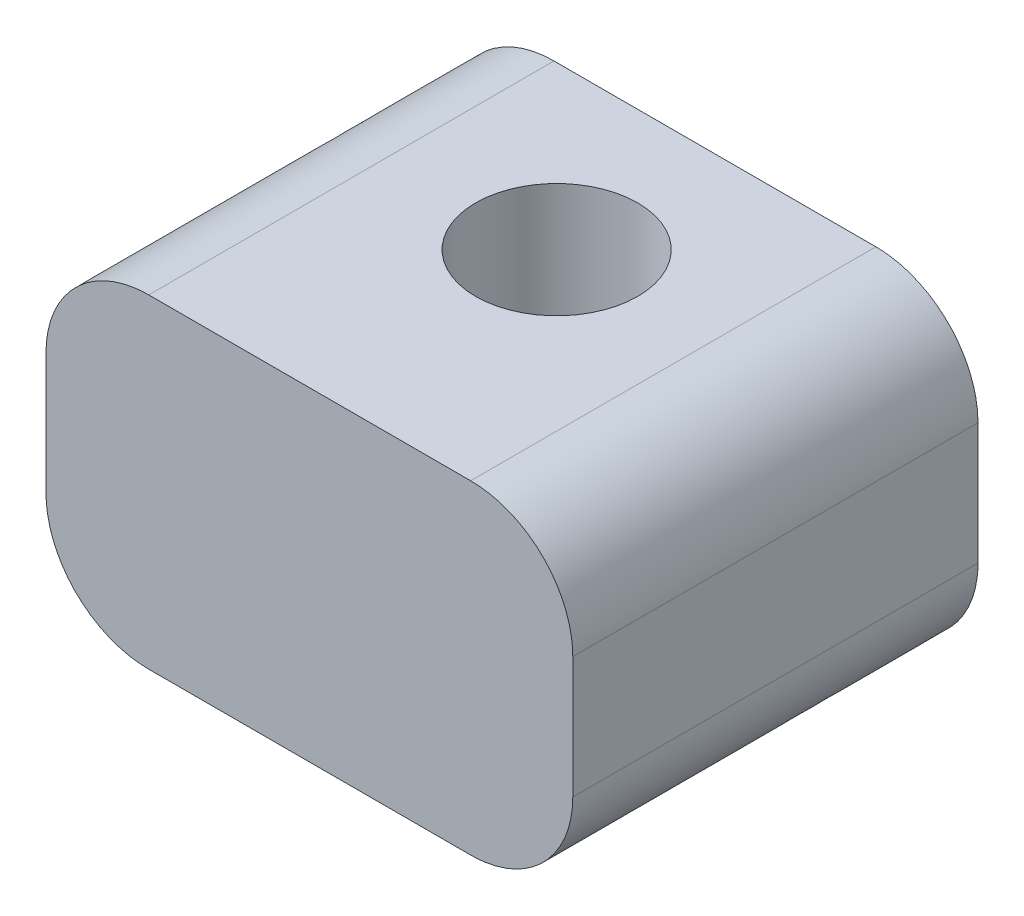
SolidWorks part; units mm, degrees
ref_plane "Plan de face" through (0, 0, 0) normal (0, 0, 1) x (1, 0, 0)
ref_plane "Plan de dessus" through (0, 0, 0) normal (0, 1, 0) x (1, 0, 0)
ref_plane "Plan de droite" through (0, 0, 0) normal (1, 0, 0) x (0, 0, -1)
sketch "Esquisse1" plane through (0, 0, 0) normal (0, 0, 1) x (1, 0, 0)
  line L0 (38.7855, 40.6141) -> (-40.6517, 40.6141)
  line L1 (-40.6517, -39.3859) -> (38.7855, -39.3859)
  line L2 (-66.0178, 15.6141) -> (-66.0178, -14.3859)
  line L3 (63.9822, -14.3859) -> (63.9822, 15.6141)
  spline S0 degree 3 poles (-40.6517, 40.6141) (-42.3144, 40.6141) (-43.95, 40.4545) (-46.3643, 39.9852) (-47.1625, 39.7902) (-48.7455, 39.3212) (-49.5335, 39.0456) (-51.8287, 38.1155) (-53.2814, 37.3559) (-55.3454, 36.0087) (-56.0141, 35.5248) (-57.3112, 34.4845) (-57.9289, 33.9366) (-59.6913, 32.2135) (-60.7465, 30.9591) (-62.1457, 28.9152) (-62.5826, 28.2035) (-63.3749, 26.7553) (-63.7328, 26.0159) (-64.3733, 24.5068) (-64.6559, 23.7372) (-65.1449, 22.1674) (-65.3517, 21.3656) (-65.851, 18.9232) (-66.0178, 17.2774) (-66.0178, 15.6141) knots 0 0 0 0 0.125 0.125 0.1875 0.1875 0.25 0.25 0.375 0.375 0.4375 0.4375 0.5 0.5 0.625 0.625 0.6875 0.6875 0.75 0.75 0.8125 0.8125 0.875 0.875 1 1 1 1
  spline S1 degree 3 poles (-66.0178, -14.3859) (-66.0178, -16.0489) (-65.8511, -17.6833) (-65.3617, -20.0941) (-65.1584, -20.8909) (-64.6695, -22.4703) (-64.383, -23.2539) (-63.4189, -25.5311) (-62.6329, -26.97) (-61.4734, -28.6704) (-61.2326, -29.0056) (-60.7328, -29.6658) (-60.4732, -29.9916) (-59.6752, -30.9436) (-59.1156, -31.5475) (-57.3566, -33.2698) (-56.0777, -34.2996) (-54.3434, -35.4353) (-53.9899, -35.6547) (-53.2767, -36.0734) (-52.9162, -36.2733) (-51.8231, -36.8456) (-50.3347, -37.5353) (-48.7852, -38.0799) (-47.2049, -38.551) (-46.3956, -38.7503) (-43.9577, -39.2265) (-42.314, -39.3859) (-40.6517, -39.3859) knots 0 0 0 0 0.125 0.125 0.1875 0.1875 0.25 0.25 0.375 0.375 0.40625 0.40625 0.4375 0.4375 0.5 0.5 0.625 0.625 0.65625 0.65625 0.6875 0.6875 0.75 0.8125 0.8125 0.875 0.875 1 1 1 1
  spline S2 degree 3 poles (38.7855, -39.3859) (40.4427, -39.3859) (42.0725, -39.2254) (44.4779, -38.7532) (45.2731, -38.557) (46.85, -38.0851) (47.6344, -37.808) (49.9178, -36.8733) (51.3625, -36.1103) (53.4143, -34.7577) (54.0799, -34.271) (55.3664, -33.2286) (55.9787, -32.68) (57.7259, -30.9545) (58.7717, -29.6987) (60.1578, -27.6532) (60.5896, -26.9422) (61.3723, -25.4968) (62.0795, -24.0208) (62.638, -22.4845) (63.1211, -20.9176) (63.3256, -20.1162) (63.8177, -17.6832) (63.9822, -16.0434) (63.9822, -14.3859) knots 0 0 0 0 0.125 0.125 0.1875 0.1875 0.25 0.25 0.375 0.375 0.4375 0.4375 0.5 0.5 0.625 0.625 0.6875 0.6875 0.75 0.8125 0.8125 0.875 0.875 1 1 1 1
  spline S3 degree 3 poles (63.9822, 15.6141) (63.9822, 17.2713) (63.8178, 18.9005) (63.3348, 21.304) (63.1341, 22.0984) (62.6516, 23.6734) (62.3685, 24.4555) (61.4156, 26.7293) (60.6385, 28.1665) (59.4915, 29.8658) (59.2532, 30.2007) (58.7587, 30.8607) (58.5017, 31.1865) (57.7105, 32.1401) (57.1555, 32.7451) (55.4107, 34.4707) (54.1418, 35.5028) (52.4205, 36.6417) (52.0688, 36.8621) (51.3592, 37.283) (51.0004, 37.484) (49.9126, 38.0593) (48.4315, 38.7524) (46.8897, 39.2998) (45.3171, 39.7733) (44.5117, 39.9738) (42.081, 40.4535) (40.4424, 40.6141) (38.7855, 40.6141) knots 0 0 0 0 0.125 0.125 0.1875 0.1875 0.25 0.25 0.375 0.375 0.40625 0.40625 0.4375 0.4375 0.5 0.5 0.625 0.625 0.65625 0.65625 0.6875 0.6875 0.75 0.8125 0.8125 0.875 0.875 1 1 1 1
extrude "Boss.-Extru.1" add sketch "Esquisse1" against normal blind 100 from offset 80
sketch "Esquisse3" plane through (0, 0, -20) normal (0, 0, -1) x (-1, 0, 0)
  line L0 (50.4849, -8.2739) -> (-49.5151, -8.2739)
  line L1 (50.4849, -8.2739) -> (50.4849, 7.7261)
  line L2 (50.4849, 7.7261) -> (-49.5151, 7.7261)
  line L3 (-49.5151, -8.2739) -> (-49.5151, 7.7261)
  dimension "D1" = 100
  dimension "D2" = 16
extrude "Enlèv. mat.-Extru.1" cut sketch "Esquisse3" along normal blind 80 from offset 80 offset against normal yes
fillet "Congé4" radius 11 2 edges at (49.5151, -0.2739, 60) (-50.4849, -0.2739, 60)
sketch "Esquisse4" plane through (0, -39.3859, 0) normal (0, -1, 0) x (1, 0, 0)
  line L0 (0, -38.5057) -> (0, 153.5884) construction
  line L1 (-40.6517, -20) -> (38.7855, -20) construction
  circle A0 centre (0, 20) radius 20
  dimension "D1" = 40
  dimension "D2" = 40
extrude "Enlèv. mat.-Extru.2" cut sketch "Esquisse4" along direction (0, 1, 0) on the side against the normal through all
ref_plane "Plan1" through (0, 0, 110) normal (0, 0, 1) x (1, 0, 0)
ref_plane "Plan2" through (0, -0.2739, 0) normal (0, 1, 0) x (1, 0, 0)
sketch "Esquisse9" plane through (0, -0.2739, 0) normal (0, 1, 0) x (1, 0, 0)
  line L1 (-66.0178, -80) -> (-40.6517, -80) construction
  line L2 (-53.3347, -80) -> (-91.0622, -90.1622) construction
  line L3 (-91.0622, -90.1622) -> (-57.1088, -141.6174) construction
  line L4 (-57.1088, -141.6174) -> (-105.4612, -241.7084) construction
  line L5 (-105.4612, -241.7084) -> (-54.4524, -229.4663) construction
  line L6 (-54.4524, -229.4663) -> (-56.6162, -229.9856) construction
  spline_without_curve S0
  point P8 (-91.3213, -106.1961)
  point P9 (-87.7359, -150.7572)
  point P10 (-101.5653, -255.2453)
  point P11 (0, 0)
  point P12 (-35.4919, -229.1233)
  point P13 (0, 0)
  point P14 (-107.5138, -83.8616)
  point P15 (-57.1088, -141.6174)
  point P16 (-91.0622, -90.1622)
  point P17 (-105.4612, -241.7084)
  point P18 (-15.3792, -229.1233)
  point P19 (-41.2215, -230.3816)
  point P20 (-56.6321, -229.9194)
  point P21 (-54.4524, -229.4663)
sketch "Esquisse10" plane through (0, -0.2739, 0) normal (0, 1, 0) x (1, 0, 0)
  line L1 (-18.4724, -126.8365) -> (-18.4724, -178.0821)
  line L2 (12.0596, -198.4759) -> (12.0596, -214.6059)
  line L4 (-0.631, -188.0821) -> (-8.4724, -188.0821)
  arc A0 (-5.0664, -112.8051) -> (-18.4724, -126.8365) centre (-6.8069, -124.5621) ccw
  arc A1 (-5.0664, -112.8051) -> (51.3839, -80) centre (2.5993, -61.0243) ccw
  arc A2 (-0.631, -188.0821) -> (12.0596, -198.4759) centre (-0.631, -201.0265) cw
  arc A3 (12.0596, -214.6059) -> (-2.7074, -229.1233) centre (-2.46, -214.6059) cw
  arc A4 (-8.4724, -188.0821) -> (-18.4724, -178.0821) centre (-8.4724, -178.0821) cw
  point P4 (51.3839, -80)
  point P5 (0, 0)
  point P14 (0, 0)
  point P16 (-3.0808, -227.941)
  point P19 (51.3839, -80)
  point P20 (51.3839, -80)
  point P21 (51.3839, -80)
  point P22 (0, 0)
  point P23 (-35.4919, -228.175)
  point P24 (0, 0)
  point P25 (0, 0)
  point P26 (-2.9087, -228.2681)
  point P27 (-2.46, -229.1233)
  point P28 (0, 0)
  point P29 (-18.4724, -126.8365)
  dimension "D1" = 10
ref_plane "Plan3" through (0, 0, 80) normal (0, 0, 1) x (1, 0, 0)
ref_plane "Plan4" through (0, 0, 145) normal (0, 0, 1) x (1, 0, 0)
ref_plane "Plan5" through (0, 0, 205) normal (0, 0, 1) x (1, 0, 0)
sketch "Esquisse11" plane through (0, 0, 205) normal (0, 0, 1) x (1, 0, 0)
  arc A0 (-45.833, -28.1823) -> (-45.833, 27.6345) centre (-47.1833, -0.2739) cw
  point P3 (0, 0)
  point P4 (0, 0)
  point P5 (-75.1243, -0.2739)
  point P6 (0, 0)
  point P8 (0, 0)
  point P9 (-45.833, -28.1823)
sketch "Esquisse13" plane through (0, 0, 145) normal (0, 0, 1) x (1, 0, 0)
  arc A0 (-46.6818, -33.6236) -> (-46.6818, 33.0759) centre (-52.2905, -0.2739) ccw
  point P3 (0, 0)
  point P4 (-55.8531, -158.9084)
  point P5 (0, 0)
  point P6 (-18.4724, -0.2739)
  point P7 (-44.6691, 27.6345)
  point P8 (-49.7035, -28.1823)
  point P9 (-41.5703, -28.1823)
  point P10 (0, 0)
  point P11 (-46.6818, 33.0759)
sketch "Esquisse14" plane through (0, 0, 80) normal (0, 0, 1) x (1, 0, 0)
  arc A0 (-28.3347, -25.2739) -> (-28.3347, 24.7261) centre (-28.3347, -0.2739) cw
  point P3 (0, 0)
  point P4 (0, 0)
  point P7 (0, 0)
  point P9 (-53.3347, -0.2739)
  point P10 (-29.0951, -32.4838)
  point P11 (-32.1141, -28.1823)
  point P13 (-31.8083, -47.8429)
  point P14 (-39.1351, -37.3037)
  dimension "D1" = 25
  dimension "D2" = 50
sketch "Esquisse15" plane through (0, 0, 205) normal (0, 0, 1) x (1, 0, 0)
  arc A0 (4.7651, -26.4484) -> (4.7651, 25.9006) centre (-38.548, -0.2739) ccw
  point P3 (0, 0)
  point P4 (12.0596, -0.2739)
  point P6 (-9.9091, -24.6097)
  point P7 (-8.2101, -28.1823)
  point P8 (0, -25.7805)
  point P9 (4.6789, 27.7989)
  point P10 (4.7651, 25.9006)
sketch "Esquisse16" plane through (0, 0, 80) normal (0, 0, 1) x (1, 0, 0)
  arc A0 (26.3839, -25.2739) -> (26.3839, 24.7261) centre (26.3839, -0.2739) ccw
  point P3 (0, 0)
  point P4 (51.3839, -0.2739)
  point P5 (22.7003, 36.756)
  point P6 (14.7893, -33.7618)
  point P8 (27.0034, 44.4485)
  point P9 (20.1916, 25.8335)
  point P10 (26.3839, -25.2739)
  point P11 (30.1459, -24.9892)
  dimension "D1" = 25
  dimension "D2" = 50
other "Surface frontière18"
other "Surface frontière19"
